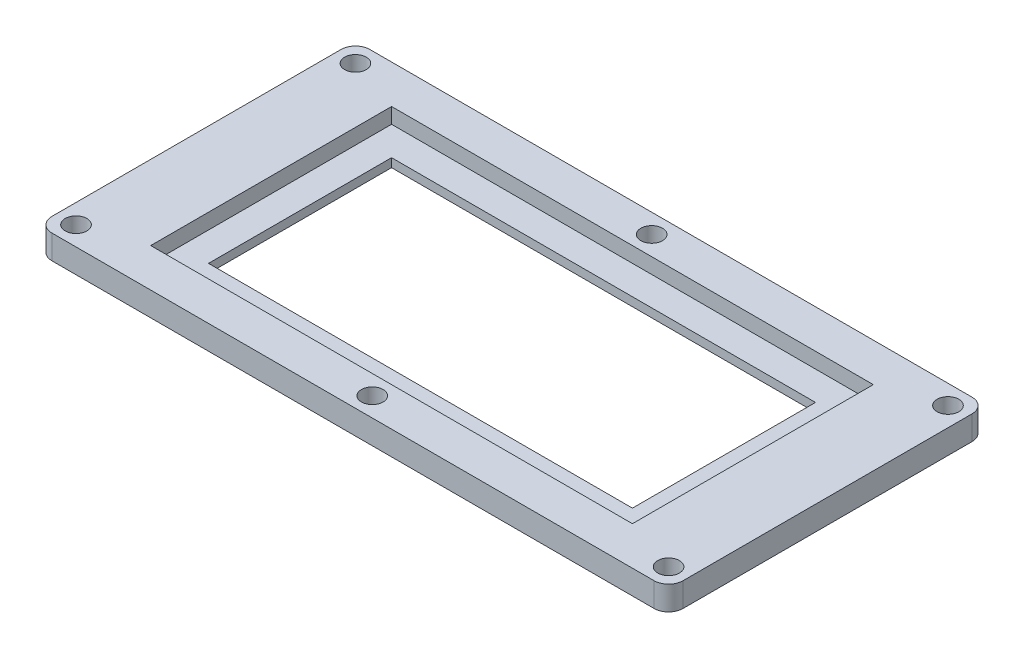
SolidWorks part; units mm, degrees
ref_plane "Front Plane" through (0, 0, 0) normal (0, 0, 1) x (1, 0, 0)
ref_plane "Top Plane" through (0, 0, 0) normal (0, 1, 0) x (1, 0, 0)
ref_plane "Right Plane" through (0, 0, 0) normal (1, 0, 0) x (0, 0, -1)
sketch "Sketch1" plane through (0, 0, 0) normal (0, 1, 0) x (1, 0, 0)
  line L1 (-65.5, -33) -> (65.5, -33)
  line L2 (-65.5, -33) -> (-65.5, 33)
  line L3 (-65.5, 33) -> (65.5, 33)
  line L4 (65.5, -33) -> (65.5, 33)
  line L5 (-65.5, -33) -> (65.5, 33) construction
  line L6 (-65.5, 33) -> (65.5, -33) construction
  point P0 (0, 0)
  dimension "D1" = 131
  dimension "D2" = 66
extrude "Boss-Extrude1" add sketch "Sketch1" along normal blind 5
fillet "Fillet1" radius 3 4 edges at (65.5, 2.5, -33) (-65.5, 2.5, -33) (65.5, 2.5, 33) (-65.5, 2.5, 33)
sketch "Sketch2" plane through (0, 5, 0) normal (0, 1, 0) x (1, 0, 0)
  line L0 (-65.5, 30) -> (-65.5, -30) construction
  line L1 (-62.5, -33) -> (62.5, -33) construction
  line L2 (65.5, -30) -> (65.5, 30) construction
  line L3 (62.5, 33) -> (-62.5, 33) construction
  circle A0 centre (-61.5, 29) radius 2.25
  circle A1 centre (61.5, 29) radius 2.25
  circle A2 centre (61.5, -29) radius 2.25
  circle A3 centre (-61.5, -29) radius 2.25
  circle A4 centre (0, 29) radius 2.25
  circle A5 centre (0, -29) radius 2.25
  point P12 (0, 0)
  point P13 (0, 0)
  point P14 (0, 0)
  point P15 (0, 0)
  dimension "D1" = 4.5
  dimension "D2" = 4
  dimension "D3" = 4
  dimension "D4" = 4
  dimension "D5" = 4
extrude "Cut-Extrude1" cut sketch "Sketch2" against normal through all
sketch "Sketch3" plane through (0, 5, 0) normal (0, 1, 0) x (1, 0, 0)
  line L1 (50, -25) -> (-50, -25)
  line L2 (50, -25) -> (50, 25)
  line L3 (50, 25) -> (-50, 25)
  line L4 (-50, -25) -> (-50, 25)
  line L5 (50, -25) -> (-50, 25) construction
  line L6 (50, 25) -> (-50, -25) construction
  point P0 (0, 0)
  dimension "D1" = 50
  dimension "D2" = 100
extrude "Cut-Extrude2" cut sketch "Sketch3" against normal blind 3.2
sketch "Sketch4" plane through (0, 1.8, 0) normal (0, 1, 0) x (1, 0, 0)
  line L25 (44, -19) -> (44, 19)
  line L26 (-44, -19) -> (44, -19)
  line L27 (-44, 19) -> (-44, -19)
  line L28 (44, 19) -> (-44, 19)
  line L29 (44, -19) -> (44, 19)
  line L30 (-44, -19) -> (44, -19)
  line L31 (-44, 19) -> (-44, -19)
  line L32 (44, 19) -> (-44, 19)
  dimension "D1" = 6
extrude "Cut-Extrude3" cut sketch "Sketch4" against normal through all
